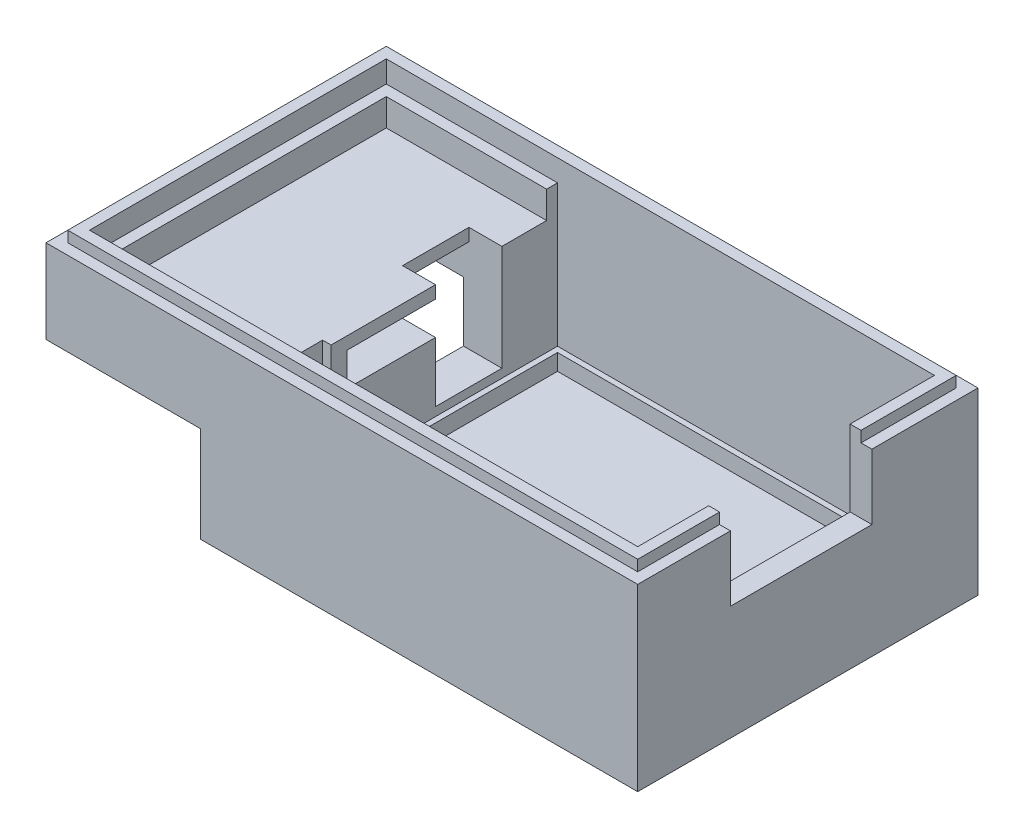
SolidWorks part; units mm, degrees
ref_plane "正面" through (0, 0, 0) normal (0, 0, 1) x (1, 0, 0)
ref_plane "平面" through (0, 0, 0) normal (0, 1, 0) x (1, 0, 0)
ref_plane "右側面" through (0, 0, 0) normal (1, 0, 0) x (0, 0, -1)
sketch "Arduino" plane through (0, 0, 0) normal (0, 1, 0) x (1, 0, 0)
  line L1 (0, 0) -> (68.58, 0)
  line L2 (0, 0) -> (0, 53.34)
  line L3 (0, 53.34) -> (68.58, 53.34)
  line L4 (68.58, 0) -> (68.58, 53.34)
  line L6 (-6.46, 38.12) -> (9.84, 38.12) construction
  line L7 (-0.5, 53.44) -> (68.68, 53.44) construction
  line L8 (-0.5, 53.44) -> (-0.5, -0.1) construction
  line L9 (-0.5, -0.1) -> (68.68, -0.1) construction
  line L10 (68.68, 53.44) -> (68.68, -0.1) construction
  line L11 (-6.46, 44.12) -> (9.84, 44.12)
  line L12 (-6.46, 44.12) -> (-6.46, 32.12)
  line L13 (-6.46, 32.12) -> (9.84, 32.12)
  line L14 (9.84, 44.12) -> (9.84, 32.12)
  line L15 (-1.96, 12.72) -> (11.74, 12.72)
  line L16 (-1.96, 12.72) -> (-1.96, 3.72)
  line L17 (-1.96, 3.72) -> (11.74, 3.72)
  line L18 (11.74, 12.72) -> (11.74, 3.72)
  line L19 (1.69, 44.12) -> (1.69, 32.12) construction
  line L20 (-1.96, 8.22) -> (11.74, 8.22) construction
  line L21 (4.89, 12.72) -> (4.89, 3.72) construction
  line L22 (34.29, 53.34) -> (34.29, 0) construction
  line L23 (-2.06, 12.82) -> (11.84, 12.82) construction
  line L24 (-2.06, 12.82) -> (-2.06, 3.62) construction
  line L25 (-2.06, 3.62) -> (11.84, 3.62) construction
  line L26 (11.84, 12.82) -> (11.84, 3.62) construction
  line L27 (-6.56, 44.22) -> (9.94, 44.22) construction
  line L28 (-6.56, 44.22) -> (-6.56, 32.02) construction
  line L29 (-6.56, 32.02) -> (9.94, 32.02) construction
  line L30 (9.94, 44.22) -> (9.94, 32.02) construction
  line L31 (0, 26.67) -> (68.58, 26.67) construction
  dimension "D1" = 68.58
  dimension "D2" = 53.34
  dimension "D3" = 0.5
  dimension "D4" = 0.1
  dimension "D5" = 0.1
  dimension "D6" = 0.1
  dimension "D7" = 12
  dimension "D8" = 16.3
  dimension "D9" = 11.45
  dimension "D10" = 32.6
  dimension "D11" = 9
  dimension "D12" = 13.7
  dimension "D13" = 29.4
  dimension "D14" = 18.45
  dimension "D15" = 0.1
  dimension "D16" = 0.1
  dimension "D17" = 0.1
  dimension "D18" = 0.1
  dimension "D19" = 0.1
  dimension "D20" = 0.1
  dimension "D21" = 0.1
  dimension "D22" = 0.1
sketch "SDカード" plane through (0, 0, 0) normal (0, 1, 0) x (1, 0, 0)
  line L0 (-0.46, 29.97) -> (25.14, 29.97) construction
  line L1 (-0.46, 43.17) -> (25.14, 43.17)
  line L2 (-0.46, 43.17) -> (-0.46, 16.77)
  line L3 (-0.46, 16.77) -> (25.14, 16.77)
  line L4 (25.14, 43.17) -> (25.14, 16.77)
  line L5 (12.34, 43.17) -> (12.34, 16.77) construction
  line L8 (-0.46, 29.97) -> (-26.3816, 29.97) construction
  line L9 (-0.51, 43.22) -> (25.19, 43.22) construction
  line L10 (-0.51, 43.22) -> (-0.51, 16.72) construction
  line L11 (-0.51, 16.72) -> (25.19, 16.72) construction
  line L12 (25.19, 43.22) -> (25.19, 16.72) construction
  line L14 (0, 26.67) -> (68.58, 26.67) construction
  line L15 (34.29, 53.34) -> (34.29, 0) construction
  dimension "D1" = 26.4
  dimension "D2" = 25.6
  dimension "D3" = 3.3
  dimension "D4" = 21.95
  dimension "D5" = 0.1
  dimension "D6" = 0.1
  dimension "D7" = 0.1
  dimension "D8" = 0.1
sketch "LCD" plane through (0, 0, 0) normal (0, 1, 0) x (1, 0, 0)
  line L0 (-31.77, 22.22) -> (68.84, 22.22) construction
  line L1 (53.23, 37.22) -> (-31.77, 37.22)
  line L2 (53.23, 37.22) -> (53.23, 7.22)
  line L3 (53.23, 7.22) -> (-31.77, 7.22)
  line L4 (-31.77, 37.22) -> (-31.77, 7.22)
  line L5 (68.58, 0) -> (68.58, 53.34) construction
  line L6 (26.34, 37.22) -> (26.34, 7.22) construction
  line L8 (0, 26.67) -> (68.58, 26.67) construction
  dimension "D1" = 4.45
  dimension "D2" = 30
  dimension "D3" = 85
  dimension "D4" = 15.35
sketch "ｽｹｯﾁ6" plane through (0, 0, 0) normal (0, 1, 0) x (1, 0, 0)
  line L0 (-0.5, -0.1) -> (68.68, -0.1) construction
  line L1 (72.78, 58.44) -> (-35.97, 58.44)
  line L2 (72.78, 58.44) -> (72.78, -4.1)
  line L3 (72.78, -4.1) -> (-35.97, -4.1)
  line L4 (-35.97, 58.44) -> (-35.97, -4.1)
  line L6 (-0.5, 53.44) -> (68.68, 53.44) construction
  line L7 (-31.77, 37.22) -> (-31.77, 7.22) construction
  line L9 (68.58, 0) -> (68.58, 53.34) construction
  dimension "D1" = 4
  dimension "D2" = 4.2
  dimension "D3" = 5
  dimension "D4" = 4.2
sketch "ｽｹｯﾁ7" plane through (0, 0, 0) normal (0, 0, 1) x (1, 0, 0)
  line L0 (0, 14.2) -> (-29.2224, 14.2) construction
  line L1 (68.58, 0) -> (0, 0)
  line L2 (68.58, 0) -> (68.58, 1.6)
  line L3 (68.58, 1.6) -> (0, 1.6)
  line L4 (0, 0) -> (0, 1.6)
  line L5 (68.58, 1.6) -> (0, 1.6)
  line L6 (68.58, 1.6) -> (68.58, 12.6)
  line L7 (68.58, 12.6) -> (0, 12.6)
  line L8 (0, 1.6) -> (0, 12.6)
  line L9 (0, 12.6) -> (68.58, 12.6)
  line L10 (0, 12.6) -> (0, 14.2)
  line L11 (0, 14.2) -> (68.58, 14.2)
  line L12 (68.58, 12.6) -> (68.58, 14.2)
  line L13 (68.08, 14.2) -> (63.08, 14.2)
  line L14 (68.08, 14.2) -> (68.08, 25.4)
  line L15 (68.08, 25.4) -> (63.08, 25.4)
  line L16 (63.08, 14.2) -> (63.08, 25.4)
  line L17 (68.88, 25.4) -> (-16.12, 25.4)
  line L18 (68.88, 25.4) -> (68.88, 27)
  line L19 (68.88, 27) -> (-16.12, 27)
  line L20 (-16.12, 25.4) -> (-16.12, 27)
  line L21 (-9.82, 32) -> (61.48, 32)
  line L22 (-9.82, 32) -> (-9.82, 27)
  line L23 (-9.82, 27) -> (61.48, 27)
  line L24 (61.48, 32) -> (61.48, 27)
  line L25 (68.58, 0) -> (0, 0)
  line L26 (68.58, 0) -> (68.58, -3)
  line L27 (68.58, -3) -> (0, -3)
  line L28 (0, 0) -> (0, -3)
  dimension "D1" = 1.6
  dimension "D2" = 11
  dimension "D3" = 1.6
  dimension "D4" = 0.5
  dimension "D5" = 5
  dimension "D6" = 11.2
  dimension "D7" = 1.6
  dimension "D8" = 85
  dimension "D9" = 0.8
  dimension "D10" = 5
  dimension "D11" = 7.4
  dimension "D12" = 71.3
  dimension "D13" = 3
extrude "ﾎﾞｽ - 押し出し1" add sketch "ｽｹｯﾁ6" along normal blind 28 and the other way blind 5
sketch "ｽｹｯﾁ8" plane through (0, 28, 0) normal (0, 1, 0) x (1, 0, 0)
  line L0 (72.78, 58.44) -> (-35.97, 58.44) construction
  line L1 (-31.97, 54.44) -> (68.78, 54.44)
  line L2 (-31.97, 54.44) -> (-31.97, -0.1)
  line L3 (-31.97, -0.1) -> (68.78, -0.1)
  line L4 (68.78, 54.44) -> (68.78, -0.1)
  line L5 (-35.97, 58.44) -> (-35.97, -4.1) construction
  line L6 (-35.97, -4.1) -> (72.78, -4.1) construction
  line L7 (72.78, -4.1) -> (72.78, 58.44) construction
  dimension "D1" = 4
  dimension "D2" = 4
  dimension "D3" = 4
  dimension "D4" = 4
extrude "ｶｯﾄ - 押し出し1" cut sketch "ｽｹｯﾁ8" against normal blind 7
sketch "ｽｹｯﾁ9" plane through (0, 21, 0) normal (0, 1, 0) x (1, 0, 0)
  line L0 (-0.5, 54.44) -> (-0.5, 44.22)
  line L1 (-0.5, 53.44) -> (-0.5, -0.1) construction
  line L2 (-6.56, 44.22) -> (9.94, 44.22) construction
  line L3 (-0.5, 44.22) -> (-6.56, 44.22)
  line L4 (-6.56, 44.22) -> (-6.56, 32.02)
  line L5 (-6.56, 32.02) -> (-0.5, 32.02)
  line L6 (-6.56, 32.02) -> (9.94, 32.02) construction
  line L7 (-0.5, 32.02) -> (-0.5, 12.82)
  line L8 (-2.06, 12.82) -> (11.84, 12.82) construction
  line L9 (-0.5, 12.82) -> (-2.06, 12.82)
  line L10 (-2.06, 12.82) -> (-2.06, 3.62)
  line L11 (-2.06, 3.62) -> (-0.5, 3.62)
  line L12 (-2.06, 3.62) -> (11.84, 3.62) construction
  line L13 (-0.5, 3.62) -> (-0.5, -0.1)
  line L14 (-0.5, -0.1) -> (68.78, -0.1)
  line L15 (68.78, -0.1) -> (68.78, 54.44)
  line L16 (68.78, 54.44) -> (-0.5, 54.44)
extrude "ｶｯﾄ - 押し出し2" cut sketch "ｽｹｯﾁ9" against normal up to vertex (19.4 mm away) up to point (0, 1.6, 0)
sketch "ｽｹｯﾁ10" plane through (0, 1.6, 0) normal (0, 1, 0) x (1, 0, 0)
  line L1 (-0.5, 54.44) -> (68.68, 54.44)
  line L2 (-0.5, 54.44) -> (-0.5, -0.1)
  line L3 (-0.5, -0.1) -> (68.68, -0.1)
  line L4 (68.68, 54.44) -> (68.68, -0.1)
extrude "ｶｯﾄ - 押し出し3" cut sketch "ｽｹｯﾁ10" against normal blind 1.6
sketch "ｽｹｯﾁ11" plane through (0, 0, 0) normal (0, 1, 0) x (1, 0, 0)
  line L1 (0.5, 53.44) -> (67.68, 53.44)
  line L2 (0.5, 53.44) -> (0.5, 0.9)
  line L3 (0.5, 0.9) -> (67.68, 0.9)
  line L4 (67.68, 53.44) -> (67.68, 0.9)
  line L5 (-0.5, 53.44) -> (-0.5, -0.1) construction
  line L6 (-0.5, -0.1) -> (68.68, -0.1) construction
  line L7 (68.68, 53.44) -> (68.68, -0.1) construction
  line L8 (68.78, 54.44) -> (-31.97, 54.44) construction
  dimension "D1" = 1
  dimension "D2" = 1
  dimension "D3" = 1
  dimension "D4" = 1
extrude "ｶｯﾄ - 押し出し4" cut sketch "ｽｹｯﾁ11" against normal blind 3
sketch "ｽｹｯﾁ12" plane through (-6.56, 0, 0) normal (1, 0, 0) x (0, 0, -1)
  line L0 (44.22, 1.6) -> (44.22, 21) construction
  line L1 (32.02, 1.6) -> (44.22, 1.6)
  line L2 (32.02, 1.6) -> (32.02, 12.6)
  line L3 (32.02, 12.6) -> (44.22, 12.6)
  line L4 (44.22, 1.6) -> (44.22, 12.6)
  dimension "D1" = 11
extrude "ｶｯﾄ - 押し出し5" cut sketch "ｽｹｯﾁ12" against normal through all
sketch "ｽｹｯﾁ14" plane through (-35.97, 0, 0) normal (-1, 0, 0) x (0, 0, 1)
  line L0 (-29.97, 18.7) -> (-29.97, 14.2) construction
  line L1 (-44.22, 18.7) -> (-15.72, 18.7)
  line L2 (-44.22, 18.7) -> (-44.22, 14.2)
  line L3 (-44.22, 14.2) -> (-15.72, 14.2)
  line L4 (-15.72, 18.7) -> (-15.72, 14.2)
  line L5 (-44.22, 16.45) -> (-15.72, 16.45) construction
  line L6 (-29.97, 28) -> (-29.97, -5) construction
  line L7 (-58.44, 28) -> (4.1, 28) construction
  line L8 (-58.44, -5) -> (4.1, -5) construction
  line L9 (-58.44, -5) -> (-58.44, 28) construction
  dimension "D1" = 4.5
  dimension "D2" = 28.5
  dimension "D3" = 19.2
extrude "ｶｯﾄ - 押し出し6" cut sketch "ｽｹｯﾁ14" against normal up to next
sketch "ｽｹｯﾁ15" plane through (0, 0, 4.1) normal (0, 0, 1) x (1, 0, 0)
  line L0 (-6.56, 18.7) -> (-6.56, 21) construction
  line L1 (-35.97, -5) -> (-7.56, -5)
  line L2 (-35.97, -5) -> (-35.97, 12.6)
  line L3 (-35.97, 12.6) -> (-7.56, 12.6)
  line L4 (-7.56, -5) -> (-7.56, 12.6)
  line L5 (-35.97, 12.6) -> (-6.56, 12.6) construction
  dimension "D1" = 1
extrude "ｶｯﾄ - 押し出し7" cut sketch "ｽｹｯﾁ15" against normal up to surface (62.54 mm away) up to face at (18.405, 11.5, -58.44)
sketch "ｽｹｯﾁ16" plane through (0, 21, 0) normal (0, 1, 0) x (1, 0, 0)
  line L0 (-0.5, 54.44) -> (-0.5, 44.22) construction
  line L1 (-31.97, 54.44) -> (-0.5, 54.44)
  line L2 (-31.97, 54.44) -> (-31.97, 52.44)
  line L3 (-31.97, 52.44) -> (-0.5, 52.44)
  line L4 (-0.5, 54.44) -> (-0.5, 52.44)
  line L5 (0, 0) -> (0, 53.34) construction
  line L6 (-31.97, -0.1) -> (0, -0.1)
  line L7 (-31.97, -0.1) -> (-31.97, 1.9)
  line L8 (-31.97, 1.9) -> (0, 1.9)
  line L9 (0, -0.1) -> (0, 1.9)
  line L11 (-31.97, 52.44) -> (-29.97, 52.44)
  line L12 (-31.97, 52.44) -> (-29.97, 52.44)
  line L13 (-31.97, 1.9) -> (-29.97, 1.9)
  line L14 (-31.97, 52.44) -> (-31.97, 1.9)
  line L15 (-31.97, 1.9) -> (-29.97, 1.9)
  line L16 (-29.97, 52.44) -> (-29.97, 1.9)
  line M3 (-31.97, 54.44) -> (-31.97, -0.1)
  dimension "D1" = 2
  dimension "D2" = 2
  dimension "D3" = 2
extrude "ﾎﾞｽ - 押し出し2" add sketch "ｽｹｯﾁ16" along normal offset from surface (5 mm away) 2 contours L16 L3 L8 M3 up to face at (18.405, 28, -27.17)
sketch "ｽｹｯﾁ23" plane through (-35.97, 0, 0) normal (-1, 0, 0) x (0, 0, 1)
  line L0 (-58.44, 12.6) -> (4.1, 12.6) construction
  line L1 (-44.22, 14.2) -> (-15.72, 14.2)
  line L2 (-44.22, 14.2) -> (-44.22, 12.6)
  line L3 (-44.22, 12.6) -> (-15.72, 12.6)
  line L4 (-15.72, 14.2) -> (-15.72, 12.6)
  line L5 (-15.72, 14.2) -> (-15.72, 18.7) construction
extrude "ｶｯﾄ - 押し出し14" cut sketch "ｽｹｯﾁ23" against normal up to next
sketch "ｽｹｯﾁ25" plane through (0, 28, 0) normal (0, 1, 0) x (1, 0, 0)
  line L0 (72.78, 58.44) -> (-35.97, 58.44) construction
  line L1 (-33.97, -2.1) -> (70.78, -2.1)
  line L2 (-33.97, -2.1) -> (-33.97, 56.44)
  line L3 (-33.97, 56.44) -> (70.78, 56.44)
  line L4 (70.78, -2.1) -> (70.78, 56.44)
  line L5 (72.78, -4.1) -> (72.78, 58.44) construction
  line L6 (-35.97, -4.1) -> (72.78, -4.1) construction
  line L7 (-35.97, 58.44) -> (-35.97, -4.1) construction
  line L9 (-31.97, -0.1) -> (68.78, -0.1)
  line L10 (-31.97, -0.1) -> (-31.97, 54.44)
  line L11 (-31.97, 54.44) -> (68.78, 54.44)
  line L12 (68.78, -0.1) -> (68.78, 54.44)
  dimension "D1" = 2
  dimension "D2" = 2
  dimension "D3" = 2
  dimension "D4" = 2
extrude "ﾎﾞｽ - 押し出し3" add sketch "ｽｹｯﾁ25" along normal blind 2
sketch "ｽｹｯﾁ26" plane through (68.78, 0, 0) normal (-1, 0, 0) x (0, 0, 1)
  line L0 (0.1, 30) -> (-54.44, 30) construction
  line L1 (-38.94, 30) -> (-12.94, 30)
  line L2 (-38.94, 30) -> (-38.94, 16)
  line L3 (-38.94, 16) -> (-12.94, 16)
  line L4 (-12.94, 30) -> (-12.94, 16)
  line L5 (-58.44, -5) -> (-58.44, 28) construction
  line L6 (4.1, -5) -> (-58.44, -5) construction
  dimension "D1" = 19.5
  dimension "D2" = 26
  dimension "D3" = 21
extrude "ｶｯﾄ - 押し出し15" cut sketch "ｽｹｯﾁ26" against normal blind 4
